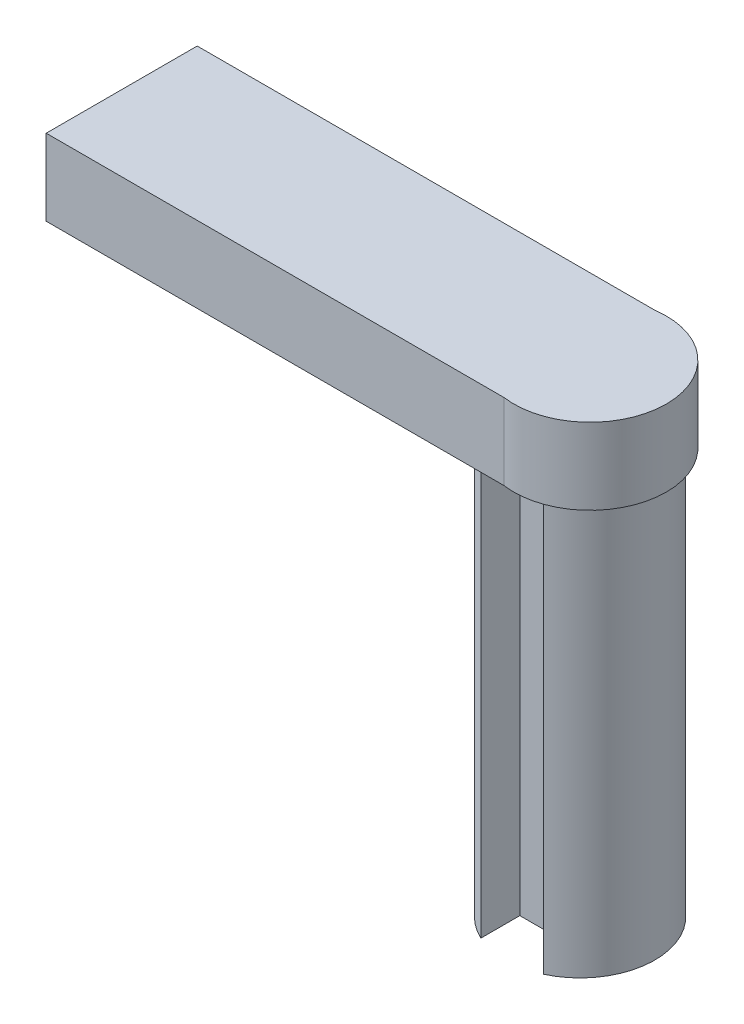
SolidWorks part; units mm, degrees
ref_plane "Front Plane" through (0, 0, 0) normal (0, 0, 1) x (1, 0, 0)
ref_plane "Top Plane" through (0, 0, 0) normal (0, 1, 0) x (1, 0, 0)
ref_plane "Right Plane" through (0, 0, 0) normal (1, 0, 0) x (0, 0, -1)
sketch "Sketch1" plane through (0, 0, 0) normal (0, 1, 0) x (1, 0, 0)
  circle A0 centre (0, 0) radius 4.9
  dimension "D1" = 9.8
extrude "Boss-Extrude1" add sketch "Sketch1" along normal blind 27
sketch "Sketch3" plane through (0, 27, 0) normal (0, 1, 0) x (1, 0, 0)
  line L0 (0, -4.9) -> (0, 4.9) construction
  line L1 (-2.05, -4.4506) -> (-2.05, -1.9006)
  line L2 (-2.05, -1.9006) -> (2.05, -1.9006)
  line L3 (2.05, -1.9006) -> (2.05, -4.4506)
  circle A0 centre (0, 0) radius 4.9 construction
  arc A1 (-2.05, -4.4506) -> (2.05, -4.4506) centre (0, 0) ccw
  dimension "D1" = 2.05
  dimension "D2" = 2.05
  dimension "D3" = 2.55
extrude "Cut-Extrude1" cut sketch "Sketch3" against normal blind 28
sketch "Sketch2" plane through (0, 27, 0) normal (0, 1, 0) x (1, 0, 0)
  line L1 (0, 4.9) -> (-30, 4.9)
  line L3 (0, -5) -> (-30, -5)
  line L4 (-30, 4.9) -> (-30, -5)
  circle A0 centre (0, 0) radius 4.9 construction
  arc A1 (0, -5) -> (0, 4.9) centre (0.7053, -0.05) ccw
  dimension "D1" = 30
extrude "Boss-Extrude2" add sketch "Sketch2" along normal blind 5
